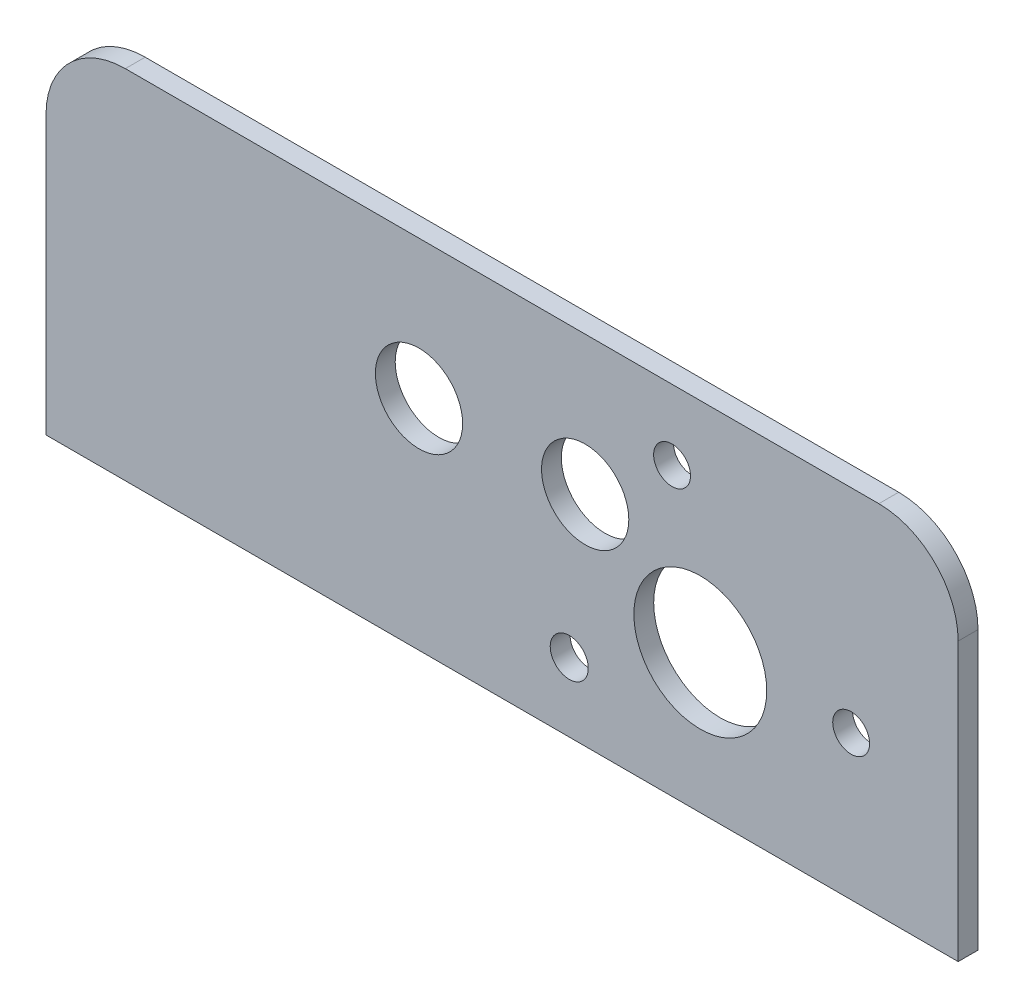
SolidWorks part; units mm, degrees
ref_plane "Front Plane" through (0, 0, 0) normal (0, 0, 1) x (1, 0, 0)
ref_plane "Top Plane" through (0, 0, 0) normal (0, 1, 0) x (1, 0, 0)
ref_plane "Right Plane" through (0, 0, 0) normal (1, 0, 0) x (0, 0, -1)
sketch "Sketch1" plane through (0, 0, 0) normal (0, 0, 1) x (1, 0, 0)
  line L1 (-115, -45) -> (115, -45)
  line L2 (-115, -45) -> (-115, 45)
  line L3 (-115, 45) -> (115, 45)
  line L4 (115, -45) -> (115, 45)
  line L5 (-115, -45) -> (115, 45) construction
  line L6 (-115, 45) -> (115, -45) construction
  point P0 (0, 0)
  dimension "D1" = 230
  dimension "D2" = 90
extrude "Boss-Extrude1" add sketch "Sketch1" along normal blind 5
fillet "Fillet1" radius 20 2 edges at (115, 45, 2.5) (-115, 45, 2.5)
sketch "Sketch2" plane through (0, 0, 5) normal (0, 0, 1) x (1, 0, 0)
  line L0 (-115, 10) -> (115, 10) construction
  line L1 (-115, 25) -> (-115, -45) construction
  line L2 (115, -45) -> (115, 25) construction
  circle A0 centre (-20.95, 10) radius 11
  circle A1 centre (20.95, 10) radius 11
  circle A2 centre (49.9769, -10) radius 16.75
  dimension "D2" = 22
  dimension "D4" = 33.5
  dimension "D1" = 41.9
  dimension "D3" = 20.95
  dimension "D5" = 35.25
  dimension "D6" = 20
  dimension "D7" = 10
extrude "Cut-Extrude1" cut sketch "Sketch2" against normal up to next
sketch "Sketch3" plane through (0, 0, 0) normal (0, 0, -1) x (-1, 0, 0)
  circle A0 centre (-42.8615, 27.3153) radius 4.65
  circle A1 centre (-88.0159, -8.5603) radius 4.65
  circle A2 centre (-16.9352, -27.6044) radius 4.8
extrude "Cut-Extrude2" cut sketch "Sketch3" against normal up to next
